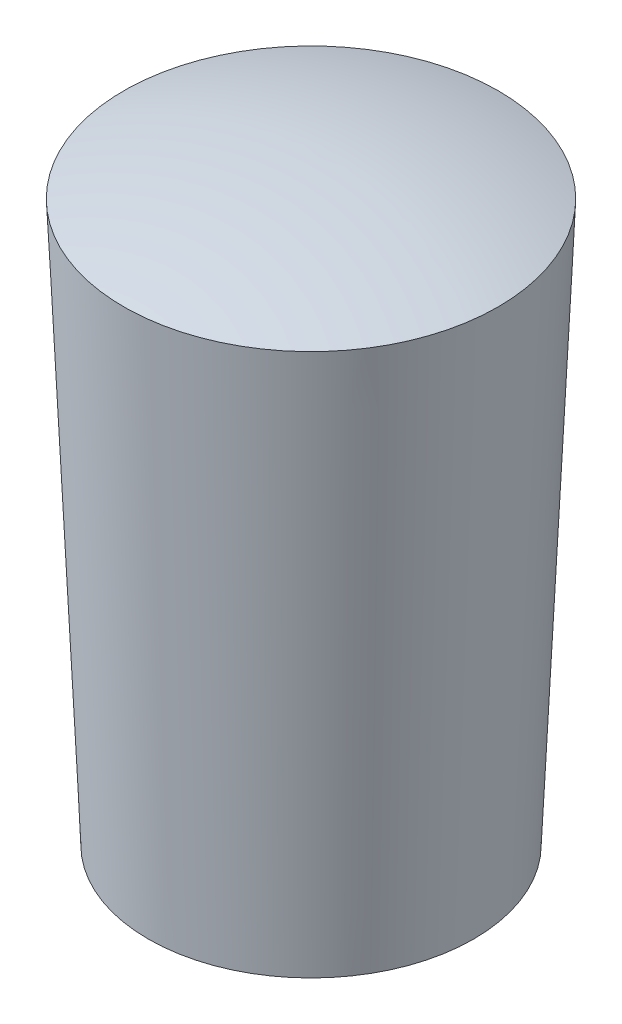
SolidWorks part; units mm, degrees
material "ABS"
ref_plane "Front Plane" through (0, 0, 0) normal (0, 0, 1) x (1, 0, 0)
ref_plane "Top Plane" through (0, 0, 0) normal (0, 1, 0) x (1, 0, 0)
ref_plane "Right Plane" through (0, 0, 0) normal (1, 0, 0) x (0, 0, -1)
sketch "Primary Sketch" plane through (0, 0, 0) normal (0, 0, 1) x (1, 0, 0)
  line L0 (0, 0) -> (0, 82.7407) construction
sketch "Base Sketch" plane through (0, 0, 0) normal (0, 0, 1) x (1, 0, 0)
  line L0 (9.69, 28.9725) -> (8.425, 0)
  line L1 (0, 0) -> (0, 82.7407) construction
  line L2 (9.69, 28.9725) -> (-30.31, 28.9725) construction
  arc A0 (9.69, 28.9725) -> (0, 30.55) centre (0, 0) ccw
  point P5 (0, 30.55)
  dimension "D1" = 2.5
  dimension "D2" = 30.55
  dimension "D3" = 8.425
  dimension "D4" = 40
revolve "Base" add sketch "Base Sketch" angle 360 about L0
